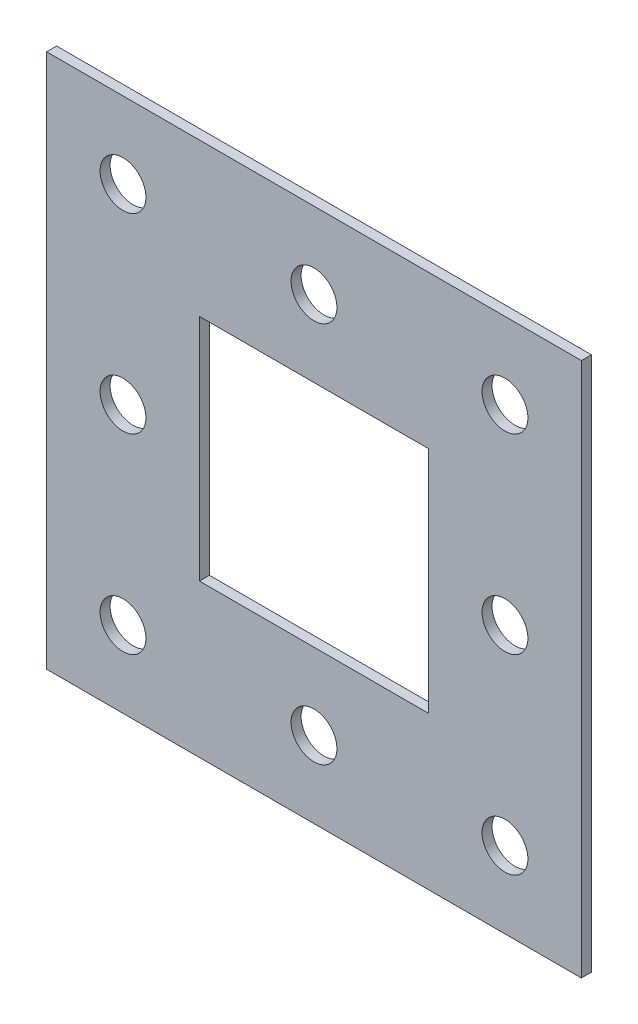
SolidWorks part; units mm, degrees
ref_plane "Front Plane" through (0, 0, 0) normal (0, 0, 1) x (1, 0, 0)
ref_plane "Top Plane" through (0, 0, 0) normal (0, 1, 0) x (1, 0, 0)
ref_plane "Right Plane" through (0, 0, 0) normal (1, 0, 0) x (0, 0, -1)
sketch "Sketch3" plane through (0, 0, 0) normal (0, 0, 1) x (1, 0, 0)
  line L1 (-35, -35) -> (35, -35)
  line L2 (-35, -35) -> (-35, 35)
  line L3 (-35, 35) -> (35, 35)
  line L4 (35, -35) -> (35, 35)
  line L5 (0, 35) -> (0, -35) construction
  line L6 (-35, 0) -> (35, 0) construction
  point P0 (0, 0)
  dimension "D1" = 70
  dimension "D2" = 70
extrude "Boss-Extrude2" add sketch "Sketch3" along normal blind 1.31
sketch "Sketch4" plane through (0, 0, 1.31) normal (0, 0, 1) x (1, 0, 0)
  line L1 (-15, -15) -> (15, -15)
  line L2 (-15, -15) -> (-15, 15)
  line L3 (-15, 15) -> (15, 15)
  line L4 (15, -15) -> (15, 15)
  line L5 (0, 15) -> (0, -15) construction
  line L6 (-15, 0) -> (15, 0) construction
  line L11 (0, 25) -> (0, -25) construction
  circle A0 centre (-25, 25) radius 3
  circle A1 centre (0, 25) radius 3
  circle A2 centre (25, 25) radius 3
  circle A3 centre (25, 0) radius 3
  circle A4 centre (25, -25) radius 3
  circle A5 centre (0, -25) radius 3
  circle A6 centre (-25, -25) radius 3
  circle A7 centre (-25, 0) radius 3
  point P0 (0, 0)
  point P4 (0, 0)
  dimension "D1" = 30
  dimension "D2" = 30
  dimension "D3" = 50
  dimension "D4" = 50
extrude "Cut-Extrude1" cut sketch "Sketch4" along normal blind 3.08 and the other way blind 31
